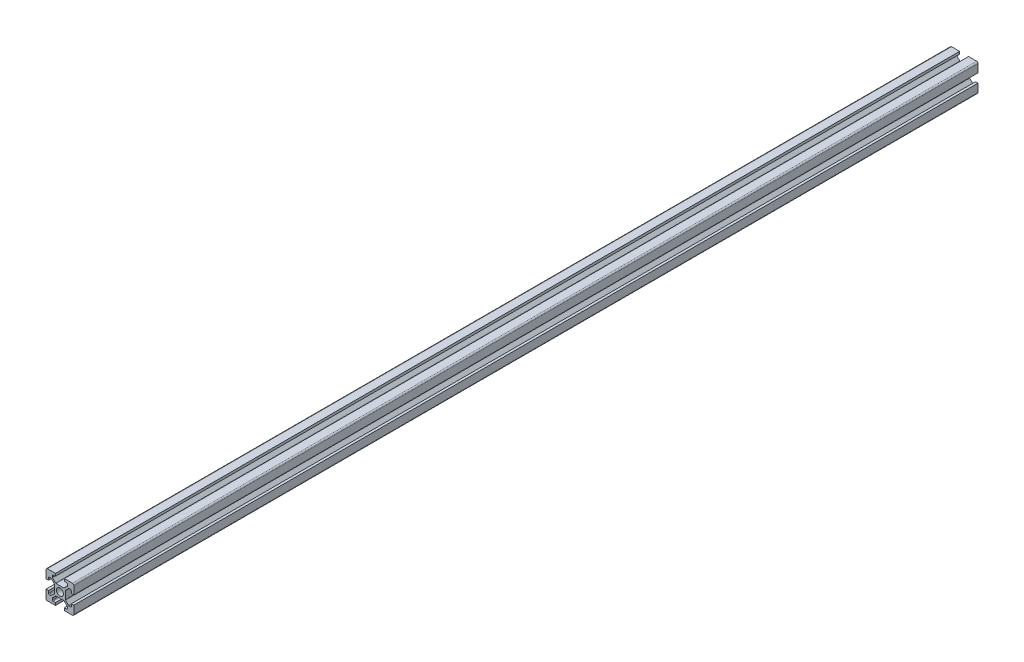
SolidWorks part; units mm, degrees
material "1060 Alloy"
ref_plane "Front Plane" through (0, 0, 0) normal (0, 0, 1) x (1, 0, 0)
ref_plane "Top Plane" through (0, 0, 0) normal (0, 1, 0) x (1, 0, 0)
ref_plane "Right Plane" through (0, 0, 0) normal (1, 0, 0) x (0, 0, -1)
sketch "Sketch1" plane through (0, 0, 0) normal (0, 0, 1) x (1, 0, 0)
  line L0 (20, 0) -> (-8.059, 28.059) construction
  line L1 (0, 0) -> (6.8, 0)
  line L2 (0, 0) -> (0, 6.8)
  line L3 (0, 20) -> (6.8, 20)
  line L4 (20, 0) -> (20, 6.8)
  line L5 (6.8, 20) -> (6.8, 18.2)
  line L6 (20, 20) -> (8.2322, 8.2322) construction
  line L7 (12.95, 6.1) -> (7.05, 6.1)
  line L8 (13.9, 7.05) -> (13.9, 12.95)
  line L9 (12.95, 13.9) -> (7.05, 13.9)
  line L10 (6.1, 7.05) -> (6.1, 12.95)
  line L11 (13.9, 6.1) -> (6.1, 13.9) construction
  line L12 (13.9, 13.9) -> (6.1, 6.1) construction
  line L13 (4.55, 16.4) -> (7.05, 13.9)
  line L14 (13.2, 18.2) -> (13.2, 20)
  line L15 (1.8, 6.8) -> (0, 6.8)
  line L16 (0, 13.2) -> (0, 20)
  line L17 (0, 13.2) -> (1.8, 13.2)
  line L18 (10, 10) -> (10, 13.9) construction
  line L19 (16.4, 4.55) -> (13.9, 7.05)
  line L20 (4.55, 16.4) -> (4.55, 18.2)
  line L21 (4.55, 18.2) -> (6.8, 18.2)
  line L22 (13.2, 18.2) -> (15.45, 18.2)
  line L23 (15.45, 18.2) -> (15.45, 16.4)
  line L24 (15.45, 16.4) -> (12.95, 13.9)
  line L25 (16.4, 4.55) -> (18.2, 4.55)
  line L26 (18.2, 4.55) -> (18.2, 6.8)
  line L27 (20, 6.8) -> (18.2, 6.8)
  line L28 (18.2, 13.2) -> (20, 13.2)
  line L29 (18.2, 13.2) -> (18.2, 15.45)
  line L30 (18.2, 15.45) -> (16.4, 15.45)
  line L31 (16.4, 15.45) -> (13.9, 12.95)
  line L32 (1.8, 4.55) -> (3.6, 4.55)
  line L33 (3.6, 15.45) -> (6.1, 12.95)
  line L34 (3.6, 15.45) -> (1.8, 15.45)
  line L35 (1.8, 15.45) -> (1.8, 13.2)
  line L36 (0, 13.2) -> (1.8, 13.2)
  line L37 (1.8, 6.8) -> (0, 6.8)
  line L38 (3.6, 4.55) -> (6.1, 7.05)
  line L39 (1.8, 6.8) -> (1.8, 4.55)
  line L40 (15.45, 3.6) -> (12.95, 6.1)
  line L41 (4.55, 3.6) -> (7.05, 6.1)
  line L42 (4.55, 1.8) -> (4.55, 3.6)
  line L43 (6.8, 1.8) -> (4.55, 1.8)
  line L44 (6.8, 1.8) -> (6.8, 0)
  line L45 (15.45, 3.6) -> (15.45, 1.8)
  line L46 (15.45, 1.8) -> (13.2, 1.8)
  line L47 (13.2, 0) -> (13.2, 1.8)
  line L48 (13.2, 20) -> (20, 20)
  line L49 (20, 13.2) -> (20, 20)
  line L50 (13.2, 0) -> (20, 0)
  line L51 (6.1, 6.1) -> (-5.5045, -5.5045) construction
  circle A0 centre (10, 10) radius 2.5
  point P25 (10, 16.4)
  point P39 (13.2, 19.1)
  point P46 (0.9, 6.8)
  dimension "D3" = 5
  dimension "D2" = 20
  dimension "D4" = 7.8
  dimension "D5" = 7.8
  dimension "D6" = 6.8
  dimension "D7" = 6.8
  dimension "D8" = 1.8
  dimension "D9" = 10.9
  dimension "D10" = 1.8
  dimension "D11" = 10.9
  dimension "D12" = 20
extrude "Boss-Extrude1" add sketch "Sketch1" along normal blind 650 contours L47 L50 L4 L27 L26 L25 L19 L8 L31 L30 L29 L28 L49 L48 L14 L22 L23 L24 L9 L13 L20 L21 L5 L3 L16 L17 L35 L34 L33 L10 L38 L32 L39 L15 L2 L1 L44 L43 L42 L41 L7 L40 L45 L46 A0
fillet "Fillet1" radius 1 4 edges at (20, 20, 325) (20, 0, 325) (0, 0, 325) (0, 20, 325)
fillet "Fillet2" radius 0.5 6 edges at (4.55, 18.2, 325) (4.55, 16.4, 325) (7.05, 13.9, 325) (15.45, 18.2, 325) (15.45, 16.4, 325) (12.95, 13.9, 325)
fillet "Fillet3" radius 0.5 6 edges at (18.2, 15.45, 325) (16.4, 15.45, 325) (13.9, 12.95, 325) (18.2, 4.55, 325) (13.9, 7.05, 325) (16.4, 4.55, 325)
fillet "Fillet4" radius 0.5 6 edges at (1.8, 15.45, 325) (3.6, 15.45, 325) (6.1, 12.95, 325) (3.6, 4.55, 325) (1.8, 4.55, 325) (6.1, 7.05, 325)
fillet "Fillet5" radius 0.5 6 edges at (7.05, 6.1, 325) (4.55, 3.6, 325) (4.55, 1.8, 325) (15.45, 1.8, 325) (15.45, 3.6, 325) (12.95, 6.1, 325)
sketch "Sketch2" plane through (0, 0, 0) normal (1, 0, 0) x (0, 0, -1)
  line L0 (-650, 10) -> (0, 10) construction
  line L1 (-650, 7.2571) -> (-650, 12.7429) construction
  line L2 (0, 11) -> (0, -11) construction
  circle A0 centre (-614.75, 10) radius 2.5
  circle A1 centre (-35.25, 10) radius 2.5
  dimension "D1" = 5
  dimension "D3" = 5
  dimension "D4" = 35.25
  dimension "D2" = 35.25
extrude "Cut-Extrude1" cut sketch "Sketch2" along normal through all both and the other way through all
sketch "Sketch3" plane through (0, 0, 0) normal (0, 1, 0) x (1, 0, 0)
  line L0 (10, -650) -> (10, 0) construction
  line L1 (12.7429, -650) -> (7.2571, -650) construction
  line L2 (-11, 0) -> (11, 0) construction
  circle A0 centre (10, -615) radius 2.5
  circle A1 centre (10, -35) radius 2.5
  dimension "D1" = 5
  dimension "D3" = 5
  dimension "D4" = 35
  dimension "D2" = 35
extrude "Cut-Extrude2" cut sketch "Sketch3" along normal through all both and the other way through all
